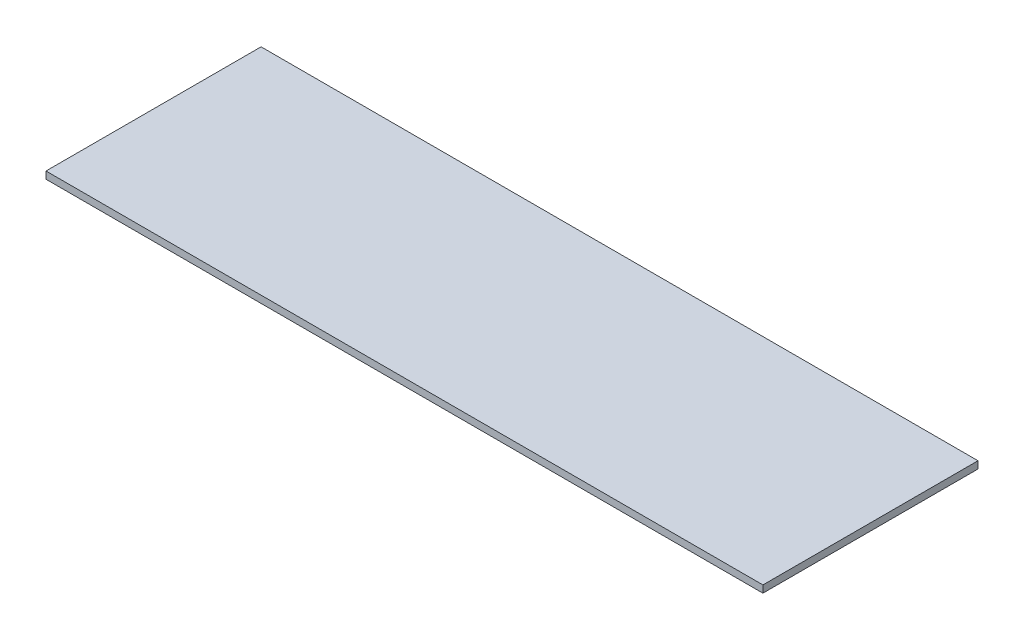
SolidWorks part; units mm, degrees
ref_plane "Front Plane" through (0, 0, 0) normal (0, 0, 1) x (1, 0, 0)
ref_plane "Top Plane" through (0, 0, 0) normal (0, 1, 0) x (1, 0, 0)
ref_plane "Right Plane" through (0, 0, 0) normal (1, 0, 0) x (0, 0, -1)
sketch "Sketch1" plane through (0, 0, 0) normal (0, 1, 0) x (1, 0, 0)
  line L1 (-120.3463, 34.632) -> (79.6537, 34.632)
  line L2 (-120.3463, 34.632) -> (-120.3463, -25.368)
  line L3 (-120.3463, -25.368) -> (79.6537, -25.368)
  line L4 (79.6537, 34.632) -> (79.6537, -25.368)
  dimension "D1" = 200
  dimension "D2" = 60
extrude "Boss-Extrude1" add sketch "Sketch1" along normal blind 2
